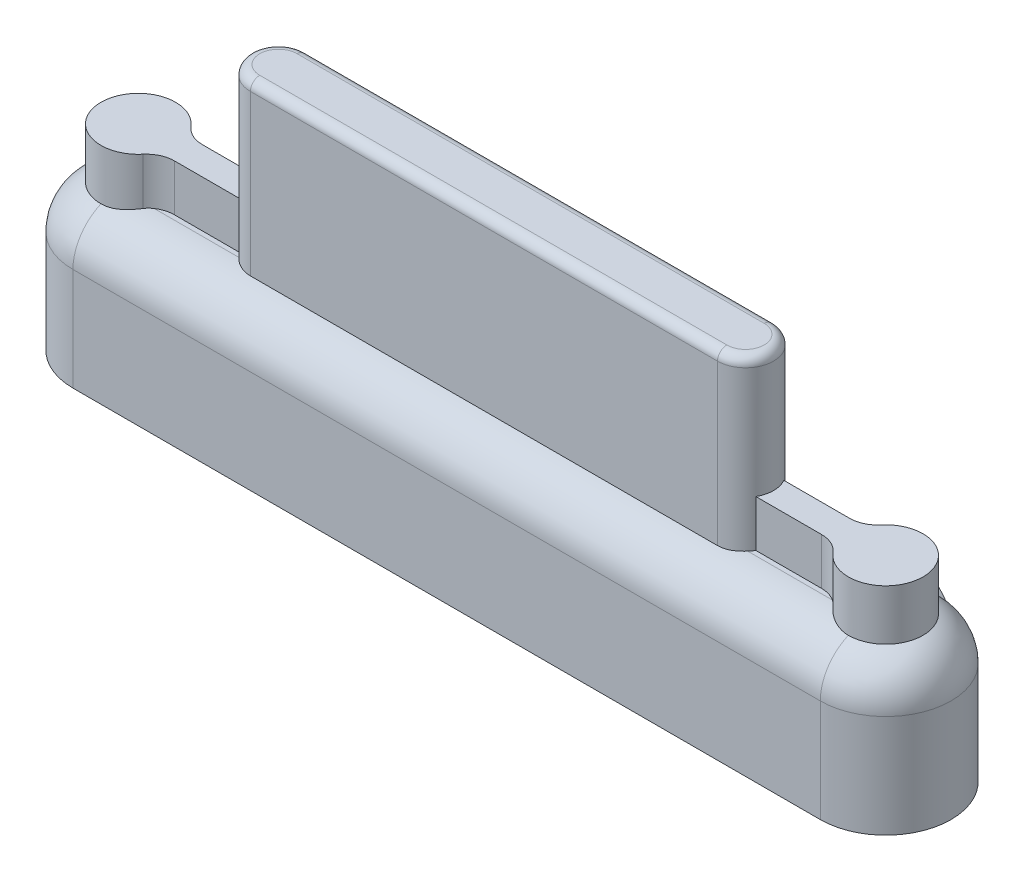
SolidWorks part; units mm, degrees
ref_plane "Front Plane" through (0, 0, 0) normal (0, 0, 1) x (1, 0, 0)
ref_plane "Top Plane" through (0, 0, 0) normal (0, 1, 0) x (1, 0, 0)
ref_plane "Right Plane" through (0, 0, 0) normal (1, 0, 0) x (0, 0, -1)
sketch "Sketch1" plane through (0, 0, 0) normal (0, 1, 0) x (1, 0, 0)
  line L0 (-20, 0) -> (20, 0) construction
  line L1 (-20, 3.5) -> (20, 3.5)
  line L2 (-20, -3.5) -> (20, -3.5)
  line L3 (-23.5, 0) -> (-23.5, 14.1667) construction
  arc A0 (-20, 3.5) -> (-20, -3.5) centre (-20, 0) ccw
  arc A1 (20, -3.5) -> (20, 3.5) centre (20, 0) ccw
  point P2 (0, 0)
  dimension "D1" = 7
  dimension "D2" = 23.5
extrude "Boss-Extrude1" add sketch "Sketch1" along normal blind 8
fillet "Fillet1" radius 2.5 4 edges at (-23.5, 8, 0) (0, 8, -3.5) (23.5, 8, 0) (0, 8, 3.5)
sketch "Sketch2" plane through (0, 8, 0) normal (0, 1, 0) x (1, 0, 0)
  line L0 (-12.5, 0) -> (12.5, 0) construction
  line L1 (-12.5, 1.5) -> (12.5, 1.5)
  line L2 (-12.5, -1.5) -> (12.5, -1.5)
  line L3 (14, 0) -> (14, 4.9833) construction
  arc A0 (-12.5, 1.5) -> (-12.5, -1.5) centre (-12.5, 0) ccw
  arc A1 (12.5, -1.5) -> (12.5, 1.5) centre (12.5, 0) ccw
  point P2 (0, 0)
  dimension "D1" = 3
  dimension "D2" = 14
extrude "Boss-Extrude2" add sketch "Sketch2" along normal blind 9 and the other way blind 1
fillet "Fillet2" radius 0.5 4 edges at (-14, 17, 0) (0, 17, -1.5) (14, 17, 0) (0, 17, 1.5)
sketch "Sketch3" plane through (0, 8, 0) normal (0, 1, 0) x (1, 0, 0)
  line L0 (-17.319, 0.75) -> (-13.799, 0.75)
  line L1 (-17.319, -0.75) -> (-13.799, -0.75)
  line L2 (0, 0) -> (0, 6.737) construction
  line L3 (17.319, -0.75) -> (13.799, -0.75)
  line L4 (17.319, 0.75) -> (13.799, 0.75)
  arc A0 (-18.468, 1.2857) -> (-18.468, -1.2857) centre (-20, 0) ccw
  arc A1 (-12.5, 1.5) -> (-12.5, -1.5) centre (-12.5, 0) ccw construction
  arc A2 (-13.799, 0.75) -> (-13.799, -0.75) centre (-12.5, 0) ccw
  arc A3 (-13.618, 1) -> (-13.618, -1) centre (-12.5, 0) ccw construction
  arc A4 (-18.468, -1.2857) -> (-17.319, -0.75) centre (-17.319, -2.25) cw
  arc A5 (-17.319, 0.75) -> (-18.468, 1.2857) centre (-17.319, 2.25) cw
  arc A6 (17.319, 0.75) -> (18.468, 1.2857) centre (17.319, 2.25) ccw
  arc A7 (18.468, -1.2857) -> (17.319, -0.75) centre (17.319, -2.25) ccw
  arc A8 (13.799, 0.75) -> (13.799, -0.75) centre (12.5, 0) cw
  arc A9 (18.468, 1.2857) -> (18.468, -1.2857) centre (20, 0) cw
  dimension "D1" = 4
  dimension "D4" = 1.5
  dimension "D2" = 0.75
  dimension "D3" = 0.75
extrude "Boss-Extrude3" add sketch "Sketch3" along normal blind 2.5 and the other way blind 1
sketch "Sketch4" plane through (0, 0, 0) normal (0, -1, 0) x (1, 0, 0)
  circle A0 centre (20, 0) radius 1.25
  circle A1 centre (-20, 0) radius 1.25
  arc A2 (-20, 3.5) -> (-20, -3.5) centre (-20, 0) ccw construction
  arc A3 (20, -3.5) -> (20, 3.5) centre (20, 0) ccw construction
  dimension "D1" = 2.5
  dimension "D2" = 2.5
extrude "Cut-Extrude1" cut sketch "Sketch4" against normal blind 9
sketch "Sketch5" plane through (0, 0, 0) normal (0, -1, 0) x (1, 0, 0)
  line L0 (8.5199, 1.25) -> (-8.5199, 1.25)
  line L1 (0, 1.25) -> (0, -2.4801) construction
  line L2 (-12.25, -2.4801) -> (-12.25, -3.5)
  line L3 (20, -3.5) -> (-20, -3.5) construction
  line L4 (12.25, -2.4801) -> (12.25, -3.5)
  line L5 (12.25, -3.5) -> (-12.25, -3.5)
  line L6 (-8.5199, -2.4801) -> (8.5199, -2.4801) construction
  arc A0 (8.5199, 1.25) -> (12.25, -2.4801) centre (8.5199, -2.4801) cw
  arc A1 (-8.5199, 1.25) -> (-12.25, -2.4801) centre (-8.5199, -2.4801) ccw
  point P9 (0, 0)
  dimension "D1" = 24.5
  dimension "D2" = 4.75
extrude "Cut-Extrude2" cut sketch "Sketch5" against normal blind 4
sketch "Sketch6" plane through (0, 0, -3.5) normal (0, 0, -1) x (-1, 0, 0)
  line L0 (0, 0) -> (0, -4.9665) construction
  line L1 (-8.5199, 0) -> (8.5199, 0) construction
  line L2 (-16.25, 0.7938) -> (-13.4433, 0.7937) construction
  line L3 (-20, 0) -> (-12.25, 0) construction
  line L4 (-13.25, 3.7938) -> (-13.25, 2.126) construction
  line L5 (-12.25, 4) -> (-12.25, 0) construction
  circle A0 centre (-16.25, 3.7938) radius 3
  circle A1 centre (16.25, 3.7938) radius 3
  dimension "D1" = 6
  dimension "D2" = 0.7937
  dimension "D3" = 1
extrude "Boss-Extrude4" add sketch "Sketch6" along normal blind 1 and the other way blind 1
sketch "Sketch7" plane through (0, 0, -4.5) normal (0, 0, -1) x (-1, 0, 0)
  circle A0 centre (-16.25, 3.7938) radius 1.25
  circle A1 centre (16.25, 3.7938) radius 1.25
  circle A2 centre (16.25, 3.7938) radius 3 construction
  dimension "D1" = 2.5
  dimension "D2" = 2.5
extrude "Cut-Extrude3" cut sketch "Sketch7" against normal blind 5
